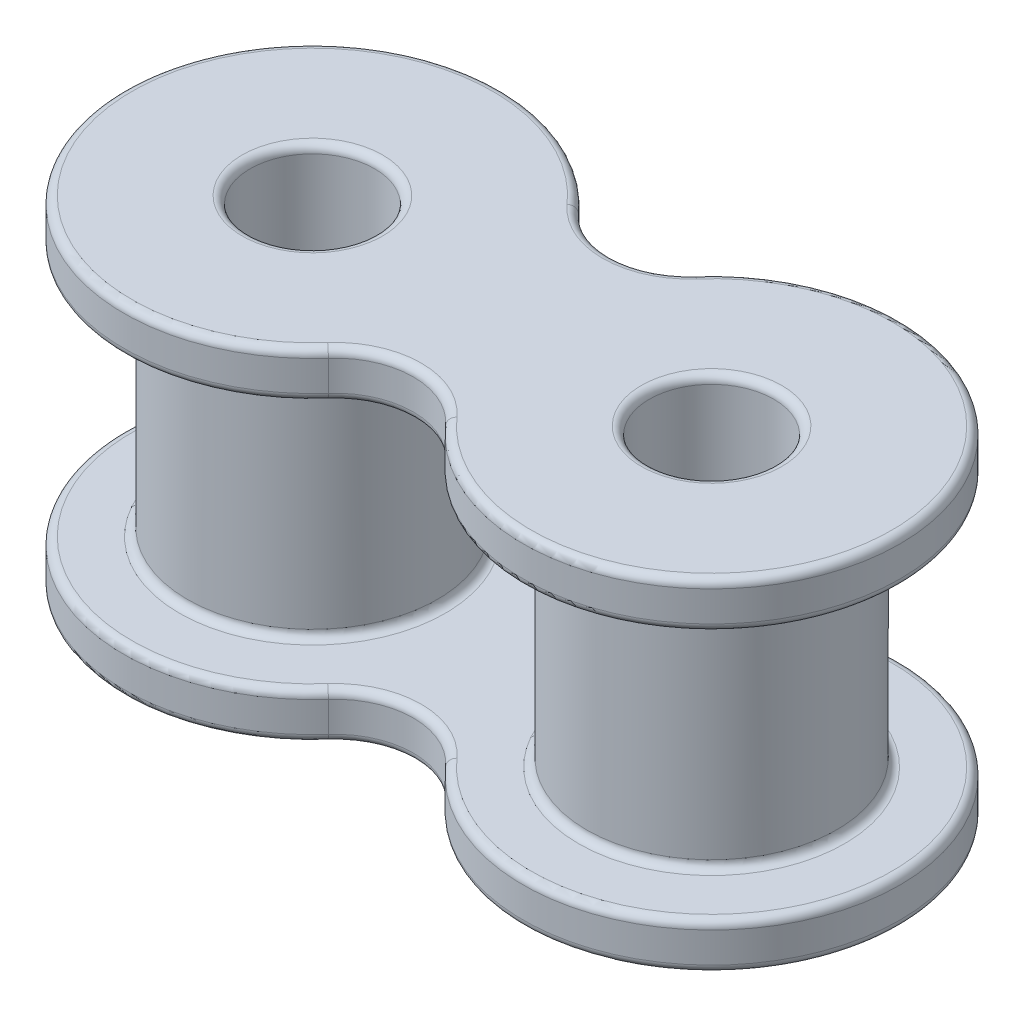
SolidWorks part; units mm, degrees
material "Alloy Steel"
ref_plane "X-Y Datum" through (0, 0, 0) normal (0, 0, 1) x (1, 0, 0)
ref_plane "X-Z Datum" through (0, 0, 0) normal (0, 1, 0) x (1, 0, 0)
ref_plane "Y-Z Datum" through (0, 0, 0) normal (1, 0, 0) x (0, 0, -1)
sketch "Sketch1" plane through (0, 0, 0) normal (0, 1, 0) x (1, 0, 0)
  line L0 (0, 9.8489) -> (0, -11.4215) construction
  line L1 (-12.6403, 0) -> (12.9549, 0) construction
  circle A0 centre (-6.35, 0) radius 1.9812
  arc A1 (-1.8654, 3.9776) -> (-1.8654, -3.9776) centre (-6.35, 0) ccw
  arc A2 (1.8654, 3.9776) -> (1.8654, -3.9776) centre (6.35, 0) cw
  circle A3 centre (6.35, 0) radius 1.9812
  arc A4 (-1.8654, 3.9776) -> (1.8654, 3.9776) centre (0, 5.6322) ccw
  arc A5 (-1.8654, -3.9776) -> (1.8654, -3.9776) centre (0, -5.6322) cw
  dimension "D1" = 11.9888
  dimension "D2" = 3.9624
  dimension "D4" = 2.4935
  dimension "D3" = 6.35
extrude "Boss-Extrude1" add sketch "Sketch1" along normal mid plane 1.4732
sketch "Sketch5" plane through (0, 0.7366, 0) normal (0, 1, 0) x (1, 0, 0)
  line L0 (0, -55) -> (0, 55) construction
  circle A0 centre (6.35, 0) radius 1.9812 construction
  circle A1 centre (6.35, 0) radius 1.9812
  circle A2 centre (-6.35, 0) radius 1.9812
  circle A3 centre (6.35, 0) radius 3.9751
  circle A4 centre (-6.35, 0) radius 3.9751
  point P9 (0, 0)
  dimension "D1" = 7.9502
extrude "Boss-Extrude2" add sketch "Sketch5" along normal blind 7.9248
fillet "Fillet" radius 0.254 12 edges at (0, 0.7366, -3.1387) (12.3444, 0.7366, 0) (0, 0.7366, 3.1387) (-12.3444, -0.7366, 0) (0, -0.7366, -3.1387) (-12.3444, 0.7366, 0) (6.35, -0.7366, -1.9812) (-6.35, -0.7366, 1.9812) (0, -0.7366, 3.1387) (12.3444, -0.7366, 0) (6.35, 0.7366, 3.9751) (-6.35, 0.7366, -3.9751)
ref_plane "Center Plane" through (0, 4.699, 0) normal (0, 1, 0) x (1, 0, 0)
mirror "Mirror2" about plane through (0, 4.699, 0) normal (0, 1, 0) of "Fillet", "Boss-Extrude1"
ref_plane "Plane1" through (0, 4.699, 0) normal (0, 1, 0) x (1, 0, 0)
ref_plane "Plane2" through (0, 4.699, 0) normal (0, 1, 0) x (1, 0, 0)
sketch "Sketch6" plane through (0, 10.1346, 0) normal (0, 1, 0) x (1, 0, 0)
  circle A0 centre (6.35, 0) radius 1.9812 construction
  circle A1 centre (6.35, 0) radius 1.9812 construction
  circle A2 centre (-6.35, 0) radius 1.9812 construction
  circle A3 centre (-6.35, 0) radius 1.9812 construction
